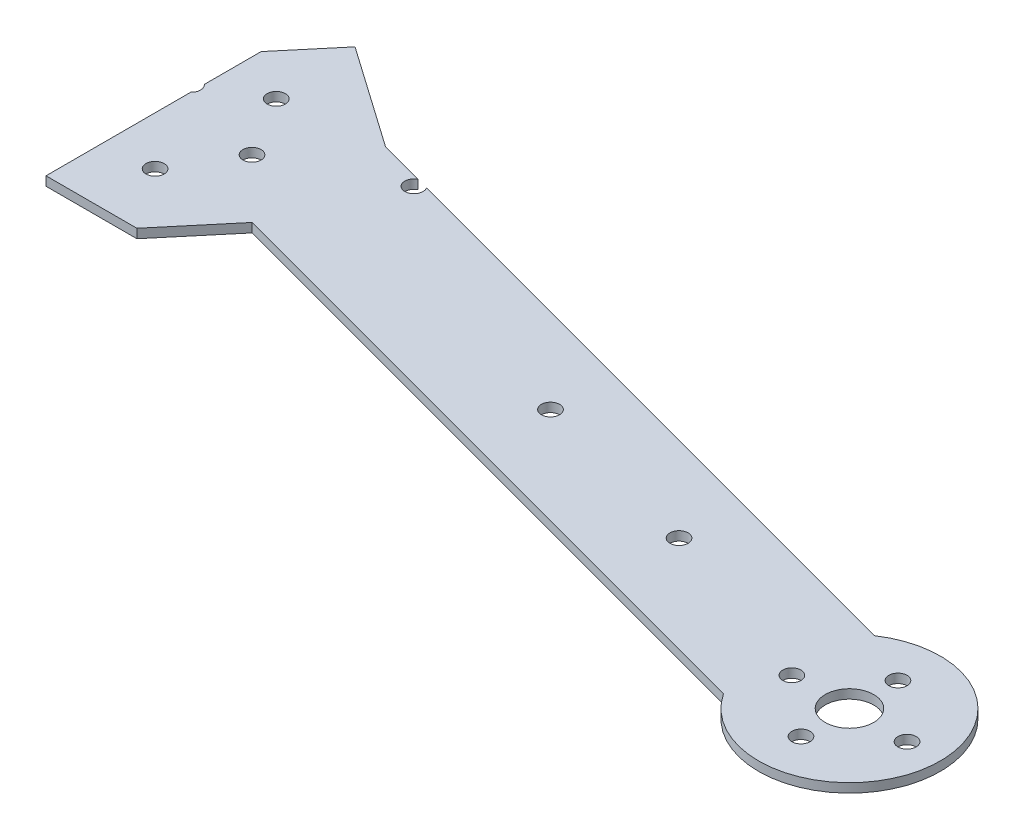
SolidWorks part; units mm, degrees
other "Markup1"
sketch "Sketch5" plane through (0, 1.5, 8.4265) normal (-0.2691, 0.6708, 0.6911) x (0.9345, 0.0084, 0.3557)
ref_plane "Front Plane" through (0, 0, 0) normal (0, 0, 1) x (1, 0, 0)
ref_plane "Top Plane" through (0, 0, 0) normal (0, 1, 0) x (1, 0, 0)
ref_plane "Right Plane" through (0, 0, 0) normal (1, 0, 0) x (0, 0, -1)
sketch "Sketch2" plane through (0, 0, 0) normal (0, 1, 0) x (1, 0, 0)
  line L25 (7.0707, -17.6306) -> (28.2625, -17.6306) construction
  line L26 (142.4295, -80.5981) -> (142.4295, -86.6558) construction
  line L27 (147.7774, -80.5981) -> (142.4295, -80.5981) construction
  line L28 (136.0028, -80.5981) -> (147.7774, -80.5981) construction
  line L29 (23.6776, -60.4195) -> (23.8633, -38.593) construction
  line L30 (0, -46.8792) -> (0, -70.7611)
  line L31 (142.4295, -80.5981) -> (142.4295, -75.2609)
  line L32 (23.8633, -38.593) -> (134.0979, -68.1247)
  line L33 (7.0707, -26.8346) -> (23.8633, -38.593)
  line L34 (0, -35.2611) -> (7.0707, -26.8346)
  line L35 (23.6776, -60.4195) -> (129.9295, -88.8896)
  line L36 (15, -70.7611) -> (23.6776, -60.4195)
  line L37 (0, -70.7611) -> (15, -70.7611)
  line L38 (0, -35.2611) -> (0, -44.6431)
  arc A14 (0, -44.6431) -> (0, -46.8792) centre (-1, -45.7611) cw
  circle A15 centre (8, -40.7611) radius 1.5
  circle A16 centre (14, -50.7611) radius 1.5
  circle A17 centre (8, -60.7611) radius 1.5
  circle A18 centre (142.4295, -80.5981) radius 4
  arc A19 (134.0979, -68.1247) -> (129.9295, -88.8896) centre (142.4295, -80.5981) cw
  circle A28 centre (142.4295, -72.5981) radius 1.5
  circle A29 centre (151.9295, -80.5981) radius 1.5
  circle A30 centre (142.4295, -88.5981) radius 1.5
  circle A31 centre (132.9295, -80.5981) radius 1.5
  point P95 (142.4295, -80.5981)
  dimension "D1" = 16
  dimension "D2" = 8
  dimension "D3" = 19
  dimension "D4" = 9.5
extrude "Boss-Extrude1" add sketch "Sketch2" along normal blind 1.5
sketch "Sketch6" plane through (0, 1.5, 0) normal (0, 1, 0) x (1, 0, 0)
  circle A0 centre (31.86, -41.9011) radius 1.5
  circle A1 centre (14, -50.7611) radius 1.5 construction
  dimension "D1" = 3
  dimension "D2" = 17.86
  dimension "D3" = 8.86
extrude "Cut-Extrude1" cut sketch "Sketch6" against normal up to surface (1.5 mm away) up to face at (151.9295, 0, 82.0981)
sketch "Sketch7" plane through (0, 1.5, 0) normal (0, 1, 0) x (1, 0, 0)
  line L0 (23.8633, -38.593) -> (134.0979, -68.1247) construction
  line L1 (142.4295, -80.5981) -> (23.994, -48.8693) construction
  circle A0 centre (75.036, -62.5434) radius 1.5
  circle A1 centre (104.0141, -70.3066) radius 1.5
  dimension "D1" = 3
  dimension "D2" = 3
  dimension "D3" = 30
  dimension "D4" = 39.77
extrude "Cut-Extrude2" cut sketch "Sketch7" against normal up to surface (1.5 mm away) up to face at (35.2404, 0, 53.3645)
